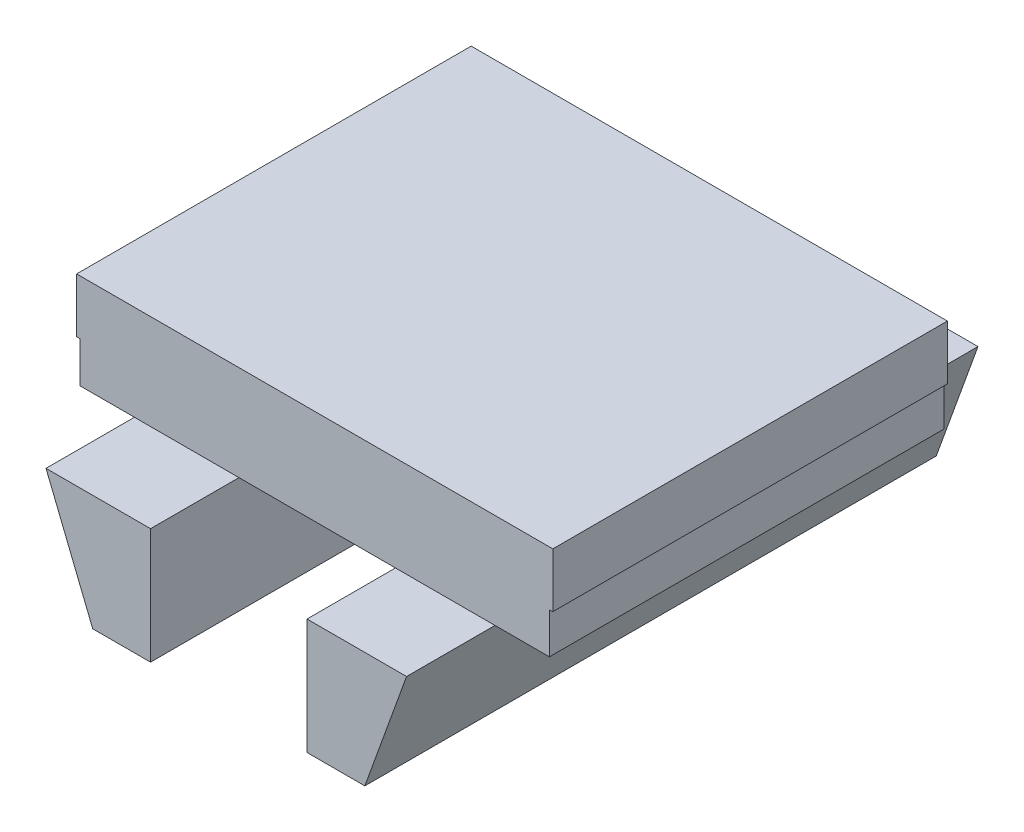
SolidWorks part; units mm, degrees
ref_plane "前视基准面" through (0, 0, 0) normal (0, 0, 1) x (1, 0, 0)
ref_plane "上视基准面" through (0, 0, 0) normal (0, 1, 0) x (1, 0, 0)
ref_plane "右视基准面" through (0, 0, 0) normal (1, 0, 0) x (0, 0, -1)
other "Configuration Table"
sketch "草图1" plane through (0, 0, 0) normal (0, 0, 1) x (1, 0, 0)
  line L1 (-18.1429, 9.1429) -> (51.8571, 9.1429)
  line L2 (-18.1429, 9.1429) -> (-18.1429, 1.1429)
  line L3 (-18.1429, 1.1429) -> (51.8571, 1.1429)
  line L4 (51.8571, 9.1429) -> (51.8571, 1.1429)
  dimension "D1" = 8
  dimension "D2" = 70
extrude "凸台-拉伸1" add sketch "草图1" along normal blind 58
sketch "草图2" plane through (0, 1.1429, 0) normal (0, -1, 0) x (1, 0, 0)
  line L0 (-18.1429, 58) -> (51.8571, 58) construction
  line L1 (-17.6429, 58) -> (51.3571, 58)
  line L2 (-17.6429, 58) -> (-17.6429, 0)
  line L3 (-17.6429, 0) -> (51.3571, 0)
  line L4 (51.3571, 58) -> (51.3571, 0)
  line L5 (-18.1429, 0) -> (51.8571, 0) construction
  line L6 (-18.1429, 58) -> (-18.1429, 0) construction
  line L7 (51.8571, 58) -> (51.8571, 0) construction
  dimension "D1" = 0.5
  dimension "D2" = 0.5
extrude "凸台-拉伸2" add sketch "草图2" along normal blind 6
sketch "草图4" plane through (0, 0, 0) normal (0, 0, 1) x (1, 0, 0)
  line L0 (-9.6429, -4.8571) -> (43.3571, -4.8571)
  line L1 (43.3571, -4.8571) -> (37.2239, -21.8531)
  line L2 (37.2239, -21.8531) -> (-2.7761, -21.8531)
  line L3 (-2.7761, -21.8531) -> (-9.6429, -4.8571)
  line L4 (51.3571, -4.8571) -> (-17.6429, -4.8571) construction
  line L5 (-17.6429, -4.8571) -> (-17.6429, 1.1429) construction
  line L6 (51.3571, -4.8571) -> (51.3571, 1.1429) construction
  dimension "D1" = 40
  dimension "D2" = 53
  dimension "D3" = 112
  dimension "D4" = 109.843
  dimension "D5" = 0
  dimension "D6" = 8
  dimension "D7" = 8
  dimension "D8" = 16.9959
extrude "凸台-拉伸3" add sketch "草图4" along normal blind 71 and the other way blind 13
sketch "草图6" plane through (0, 0, 71) normal (0, 0, 1) x (1, 0, 0)
  line L0 (5.7239, -21.8531) -> (5.7239, -4.8571)
  line L1 (-2.7761, -21.8531) -> (37.2239, -21.8531) construction
  line L2 (43.3571, -4.8571) -> (-9.6429, -4.8571) construction
  line L3 (5.7239, -4.8571) -> (28.7239, -4.8571)
  line L4 (28.7239, -4.8571) -> (28.7239, -21.8531)
  line L5 (5.7239, -21.8531) -> (28.7239, -21.8531)
  dimension "D1" = 8.5
  dimension "D2" = 23
  dimension "D3" = 8.5
extrude "切除-拉伸2" cut sketch "草图6" against normal up to next
